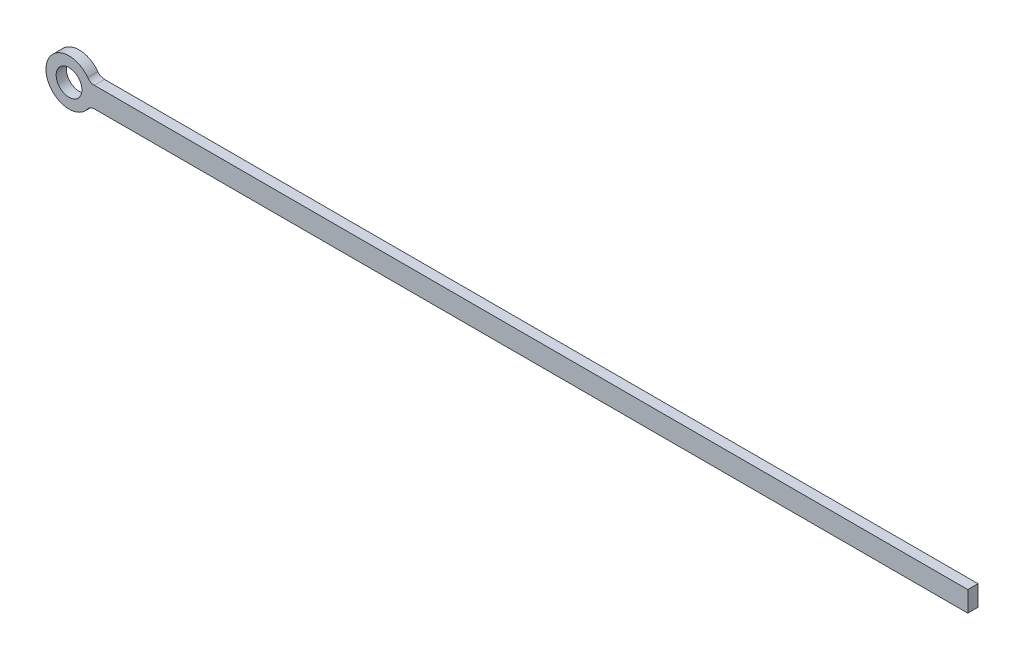
SolidWorks part; units mm, degrees
ref_plane "Front Plane" through (0, 0, 0) normal (0, 0, 1) x (1, 0, 0)
ref_plane "Top Plane" through (0, 0, 0) normal (0, 1, 0) x (1, 0, 0)
ref_plane "Right Plane" through (0, 0, 0) normal (1, 0, 0) x (0, 0, -1)
sketch "Sketch1" plane through (0, 0, 0) normal (0, 0, 1) x (1, 0, 0)
  line L0 (0, 0) -> (279.4, 0) construction
  line L1 (7.8562, 3.175) -> (279.4, 3.175)
  line L2 (279.4, 3.175) -> (279.4, -3.175)
  line L3 (279.4, -3.175) -> (7.8562, -3.175)
  circle A0 centre (0, 0) radius 4
  arc A1 (5.8022, 4.2208) -> (5.8022, -4.2208) centre (0, 0) ccw
  circle A2 centre (0, 0) radius 7.175 construction
  arc A3 (7.8562, -3.175) -> (5.8022, -4.2208) centre (7.8562, -5.715) ccw
  arc A4 (7.8562, 3.175) -> (5.8022, 4.2208) centre (7.8562, 5.715) cw
  dimension "D1" = 8
  dimension "D4" = 2.54
  dimension "D3" = 6.35
  dimension "D5" = 279.4
  dimension "D2" = 3.175
extrude "Boss-Extrude1" add sketch "Sketch1" along normal blind 3.175
